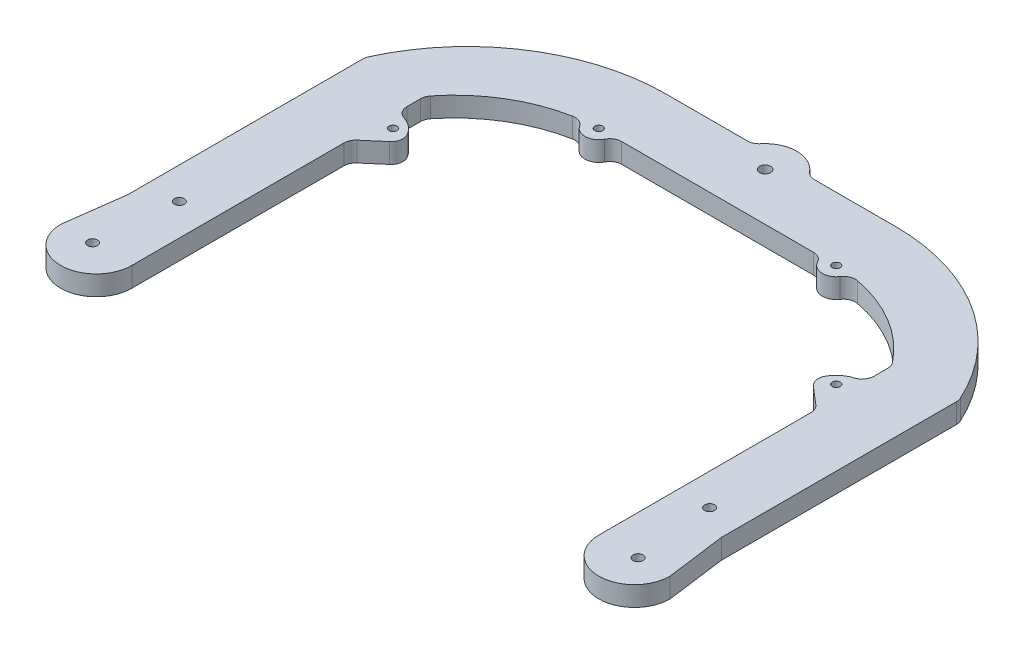
SolidWorks part; units mm, degrees
ref_plane "Front Plane" through (0, 0, 0) normal (0, 0, 1) x (1, 0, 0)
ref_plane "Top Plane" through (0, 0, 0) normal (0, 1, 0) x (1, 0, 0)
ref_plane "Right Plane" through (0, 0, 0) normal (1, 0, 0) x (0, 0, -1)
sketch "Sketch1" plane through (0, 0, 0) normal (0, 1, 0) x (1, 0, 0)
  line L0 (0, 74) -> (0, 0) construction
  line L1 (29, 74) -> (-29, 74)
  line L2 (59, 59) -> (59, 0)
  line L3 (0, 0) -> (75, 0) construction
  line L4 (75, 0) -> (75, 60)
  line L5 (0, 90) -> (0, 74) construction
  line L6 (29, 90) -> (-29, 90)
  line L7 (75, 0) -> (76.9854, -15)
  line L8 (59, 0) -> (59, -15)
  line L9 (-75, 0) -> (-76.9854, -15)
  line L10 (-59, 0) -> (-59, -15)
  line L11 (-59, 59) -> (-59, 0)
  line L12 (-75, 0) -> (-75, 60)
  arc A0 (29, 74) -> (59, 59) centre (29, 36.5) cw
  arc A1 (75, 60) -> (29, 90) centre (29, 39.7333) ccw
  arc A2 (76.9854, -15) -> (59, -15) centre (67.9927, -15) cw
  arc A3 (-76.9854, -15) -> (-59, -15) centre (-67.9927, -15) ccw
  arc A4 (-75, 60) -> (-29, 90) centre (-29, 39.7333) cw
  arc A5 (-29, 74) -> (-59, 59) centre (-29, 36.5) ccw
  circle A6 centre (67, 5) radius 1.25
  circle A7 centre (68.9157, -15) radius 1.25
  circle A8 centre (-68.9157, -15) radius 1.25
  circle A9 centre (-67, 5) radius 1.25
  dimension "D6" = 29
  dimension "D9" = 172.46
  dimension "D15" = 2.5
  dimension "D1" = 29
  dimension "D2" = 15
  dimension "D3" = 30
  dimension "D4" = 75
  dimension "D5" = 16
  dimension "D7" = 60
  dimension "D8" = 90
  dimension "D10" = 15
  dimension "D11" = 5
  dimension "D12" = 8
  dimension "D13" = 15
  dimension "D14" = 8
extrude "Boss-Extrude1" add sketch "Sketch1" along normal blind 5
sketch "Sketch2" plane through (0, 5, 0) normal (0, 1, 0) x (1, 0, 0)
  line L0 (0, 74) -> (0, 130) construction
  line L1 (-29, 74) -> (29, 74) construction
  line L2 (29, 90) -> (-29, 90) construction
  line L3 (59, 39.9867) -> (52, 45.9867)
  line L4 (59, 51.9867) -> (51.3728, 51.9867) construction
  line L5 (59, 59) -> (59, -15) construction
  line L6 (-59, 39.9867) -> (-52, 45.9867)
  arc A0 (-6.9282, 90) -> (6.9282, 90) centre (0, 86) cw
  arc A1 (26.5, 74) -> (33.4906, 73.7302) centre (30, 73.9867) ccw
  arc A2 (59, 59) -> (29, 74) centre (29, 36.5) ccw construction
  arc A3 (52, 45.9867) -> (59, 51.9867) centre (59, 44.9033) cw
  arc A4 (52, 45.9867) -> (47.1412, 38.1514) centre (54.1412, 39.2347) ccw
  arc A5 (-26.5, 74) -> (-33.4906, 73.7302) centre (-30, 73.9867) cw
  arc A6 (-52, 45.9867) -> (-59, 51.9867) centre (-59, 44.9033) ccw
  dimension "D1" = 8
  dimension "D2" = 3.5
  dimension "D5" = 22
  dimension "D3" = 22
  dimension "D4" = 30
  dimension "D6" = 12
  dimension "D7" = 6
  dimension "D8" = 4
extrude "Boss-Extrude2" add sketch "Sketch2" against normal blind 5
hole_wizard "Ø2.0 (2) Diameter Hole2" positions "Sketch6" profile "Sketch5" hole size "Ø2.0" standard "ISO" end condition through all
sketch "Sketch6" plane through (0, 5, 0) normal (0, 1, 0) x (1, 0, 0)
  point P0 (30, 73.9867)
  point P3 (56, 47.9867)
  point P5 (-30, 73.9867)
  point P8 (-56, 47.9867)
  dimension "D1" = 26
  dimension "D2" = 26
  dimension "D3" = 26
  dimension "D4" = 26
sketch "Sketch5" plane through (30, 5, -73.9867) normal (1, 0, 0) x (0, 0, 1)
  line L0 (0, 0) -> (0, 5)
  line L1 (0, 5) -> (1, 5)
  line L2 (1, 5) -> (1, 0)
  line L5 (1, 0) -> (0, 0)
  line L11 (0, -6.35) -> (0, 107.95) construction
  dimension "Thru Hole Dia." = 2
  dimension "Thru Hole Depth" = 5
fillet "Fillet2" radius 3 16 edges at (52, 2.5, -45.9867) (59, 2.5, -51.9867) (59, 2.5, -39.9867) (59, 2.5, -59) (-59, 2.5, -59) (-75, 2.5, -60) (75, 2.5, -60) (-6.9282, 2.5, -90) (6.9282, 2.5, -90) (-26.5, 2.5, -74) (-33.4906, 2.5, -73.7302) (-52, 2.5, -45.9867) (-59, 2.5, -39.9867) (-59, 2.5, -51.9867) (26.5, 2.5, -74) (33.4906, 2.5, -73.7302)
hole_wizard "Ø2.8 (2.8) Diameter Hole1" positions "Sketch8" profile "Sketch7" hole size "Ø2.8" standard "ISO" end condition through all
sketch "Sketch8" plane through (0, 5, 0) normal (0, 1, 0) x (1, 0, 0)
  arc A0 (6.1711, 91.0909) -> (-6.1711, 91.0909) centre (0, 86) ccw construction
  point P0 (0, 86)
  point P3 (0, 94)
  dimension "D1" = 8
sketch "Sketch7" plane through (0, 5, -86) normal (1, 0, 0) x (0, 0, 1)
  line L0 (0, 0) -> (0, 5)
  line L1 (0, 5) -> (1.4, 5)
  line L2 (1.4, 5) -> (1.4, 0)
  line L5 (1.4, 0) -> (0, 0)
  line L11 (0, -6.35) -> (0, 107.95) construction
  dimension "Thru Hole Dia." = 2.8
  dimension "Thru Hole Depth" = 5
